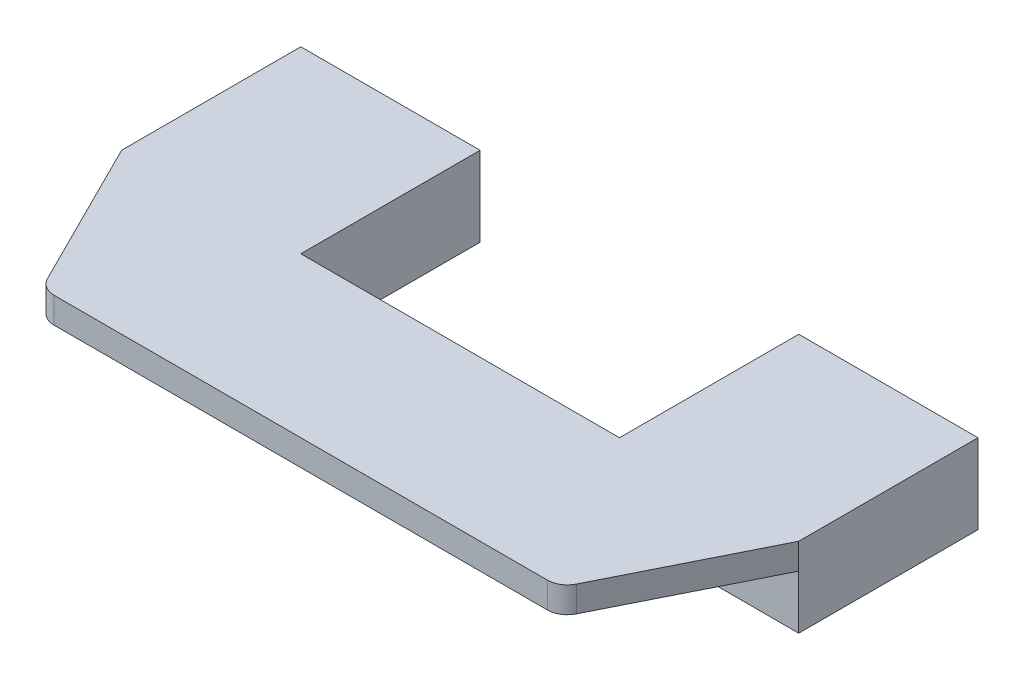
SolidWorks part; units mm, degrees
ref_plane "Alzado" through (0, 0, 0) normal (0, 0, 1) x (1, 0, 0)
ref_plane "Planta" through (0, 0, 0) normal (0, 1, 0) x (1, 0, 0)
ref_plane "Vista lateral" through (0, 0, 0) normal (1, 0, 0) x (0, 0, -1)
sketch "Croquis1" plane through (0, 0, 0) normal (0, 1, 0) x (1, 0, 0)
  line L1 (-17, 8.5) -> (17, 8.5)
  line L2 (-17, 8.5) -> (-17, -8.5)
  line L3 (-17, -8.5) -> (17, -8.5)
  line L4 (17, 8.5) -> (17, -8.5)
  line L5 (-17, 8.5) -> (17, -8.5) construction
  line L6 (-17, -8.5) -> (17, 8.5) construction
  point P0 (0, 0)
  dimension "D1" = 17
  dimension "D2" = 34
extrude "Saliente-Extruir1" add sketch "Croquis1" along normal blind 4
sketch "Croquis2" plane through (0, 4, 0) normal (0, 1, 0) x (1, 0, 0)
  line L0 (0, -12.8999) -> (0, 13.926) construction
  line L1 (17, 8.5) -> (-17, 8.5) construction
  line L2 (-8, -0.5) -> (8, -0.5)
  line L3 (-8, -0.5) -> (-8, 8.5)
  line L4 (-8, 8.5) -> (8, 8.5)
  line L5 (8, -0.5) -> (8, 8.5)
  line L6 (-8, -0.5) -> (8, 8.5) construction
  line L7 (-8, 8.5) -> (8, -0.5) construction
  point P3 (0, 4)
  dimension "D1" = 16
  dimension "D2" = 9
extrude "Cortar-Extruir1" cut sketch "Croquis2" against normal blind 5
sketch "Croquis3" plane through (0, 0, 8.5) normal (0, 0, 1) x (1, 0, 0)
  line L0 (17, 4) -> (17, 0) construction
  line L1 (-17, 0) -> (17, 0)
  line L2 (-17, 0) -> (-17, 2.7)
  line L3 (-17, 2.7) -> (17, 2.7)
  line L4 (17, 0) -> (17, 2.7)
  dimension "D1" = 2.7
extrude "Cortar-Extruir2" cut sketch "Croquis3" against normal blind 8
sketch "Croquis4" plane through (0, 4, 0) normal (0, 1, 0) x (1, 0, 0)
  line L0 (-13, -8.5) -> (13, -8.5) construction
  line L1 (-17, -8.5) -> (17, -8.5) construction
  line L2 (0, -0.328) -> (0, -11.9177) construction
  line L3 (-17, 8.5) -> (-17, -8.5) construction
  line L8 (-17, -0.5) -> (-13, -8.5)
  line L9 (-17, -8.5) -> (-17, -0.5)
  line L10 (13, -8.5) -> (17, -8.5)
  line L11 (17, -8.5) -> (17, -0.5)
  line L12 (17, -0.5) -> (13, -8.5)
  line L13 (-13, -8.5) -> (-17, -8.5)
  point P7 (0, -8.5)
  dimension "D1" = 26
  dimension "D2" = 8
extrude "Cortar-Extruir3" cut sketch "Croquis4" against normal blind 3
fillet "Redondeo3" radius 1 1 edges at (-13, 3.35, 8.5)
fillet "Redondeo4" radius 1 1 edges at (13, 3.35, 8.5)
